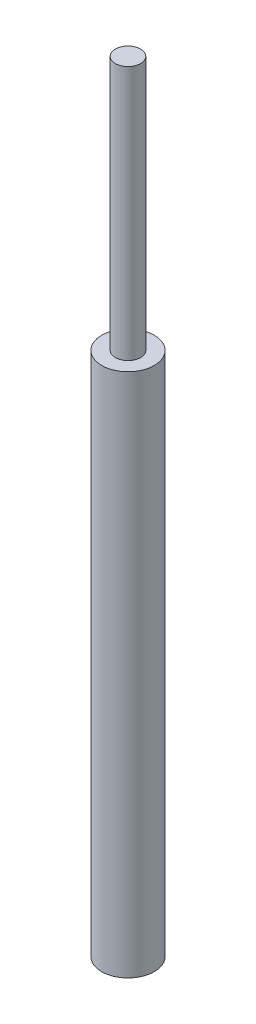
SolidWorks part; units mm, degrees
ref_plane "Front Plane" through (0, 0, 0) normal (0, 0, 1) x (1, 0, 0)
ref_plane "Top Plane" through (0, 0, 0) normal (0, 1, 0) x (1, 0, 0)
ref_plane "Right Plane" through (0, 0, 0) normal (1, 0, 0) x (0, 0, -1)
sketch "Sketch1" plane through (0, 0, 0) normal (0, 1, 0) x (1, 0, 0)
  circle A1 centre (0, 0) radius 5
  dimension "D1" = 10
extrude "Boss-Extrude1" add sketch "Sketch1" along normal mid plane 100
sketch "Sketch2" plane through (0, 50, 0) normal (0, 1, 0) x (1, 0, 0)
  circle A0 centre (0, 0) radius 2.4
  dimension "D1" = 4.8
extrude "Boss-Extrude2" add sketch "Sketch2" along normal mid plane 3
mirror "Mirror1" about plane through (0, 0, 0) normal (0, 1, 0) of "Boss-Extrude2"
sketch "Sketch3" plane through (0, 51.5, 0) normal (0, 1, 0) x (1, 0, 0)
  circle A0 centre (0, 0) radius 2.4
  dimension "D1" = 4.8
extrude "Boss-Extrude3" add sketch "Sketch3" along normal blind 47
